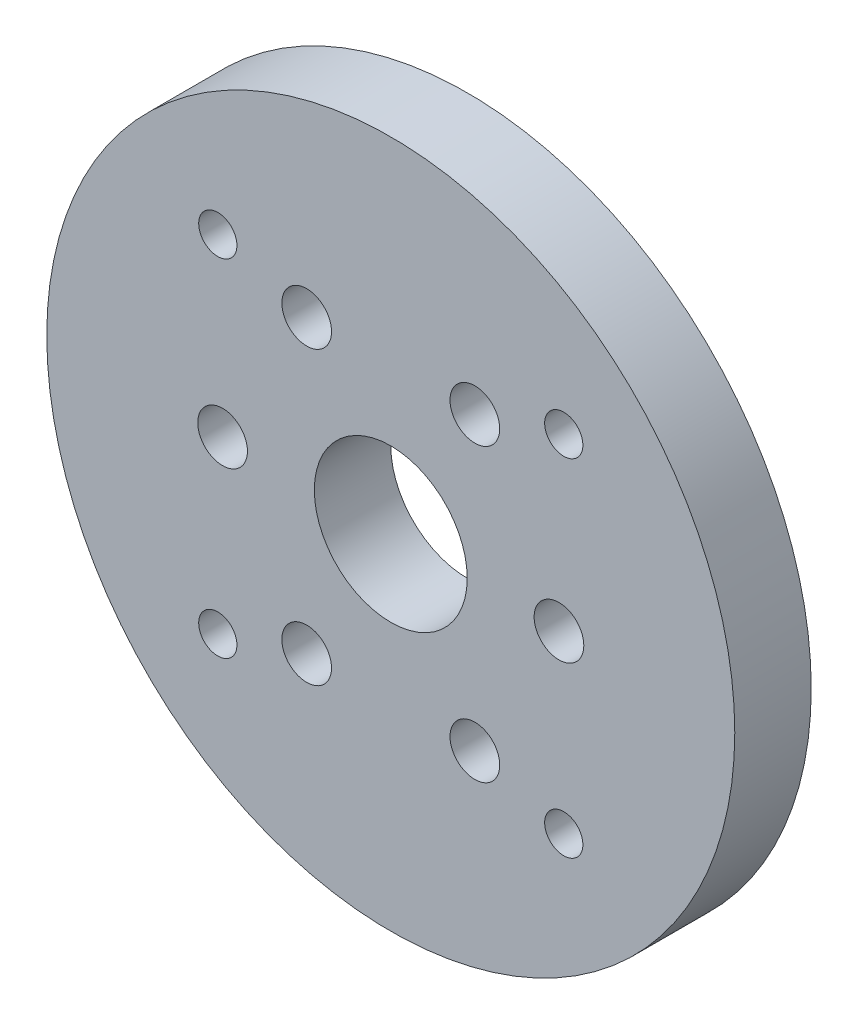
SolidWorks part; units mm, degrees
material "6061-T6 (SS)"
ref_plane "前视基准面" through (0, 0, 0) normal (0, 0, 1) x (1, 0, 0)
ref_plane "上视基准面" through (0, 0, 0) normal (0, 1, 0) x (1, 0, 0)
ref_plane "右视基准面" through (0, 0, 0) normal (1, 0, 0) x (0, 0, -1)
other "Configuration Table"
sketch "草图1" plane through (0, 0, 0) normal (0, 0, 1) x (1, 0, 0)
  circle A0 centre (0, 0) radius 45
extrude "凸台-拉伸1" add sketch "草图1" along normal blind 10
sketch "草图2" plane through (0, 0, 0) normal (0, 0, -1) x (-1, 0, 0)
  circle A0 centre (0, 0) radius 10
  circle A1 centre (-22, 0) radius 3.25
  circle A2 centre (-11, 19.0526) radius 3.25
  circle A3 centre (11, 19.0526) radius 3.25
  circle A4 centre (22, 0) radius 3.25
  circle A5 centre (11, -19.0526) radius 3.25
  circle A6 centre (-11, -19.0526) radius 3.25
  circle A7 centre (-22.6274, 22.6274) radius 2.5
  circle A8 centre (22.6274, 22.6274) radius 2.5
  circle A9 centre (22.6274, -22.6274) radius 2.5
  circle A10 centre (-22.6274, -22.6274) radius 2.5
extrude "切除-拉伸1" cut sketch "草图2" against normal blind 11
